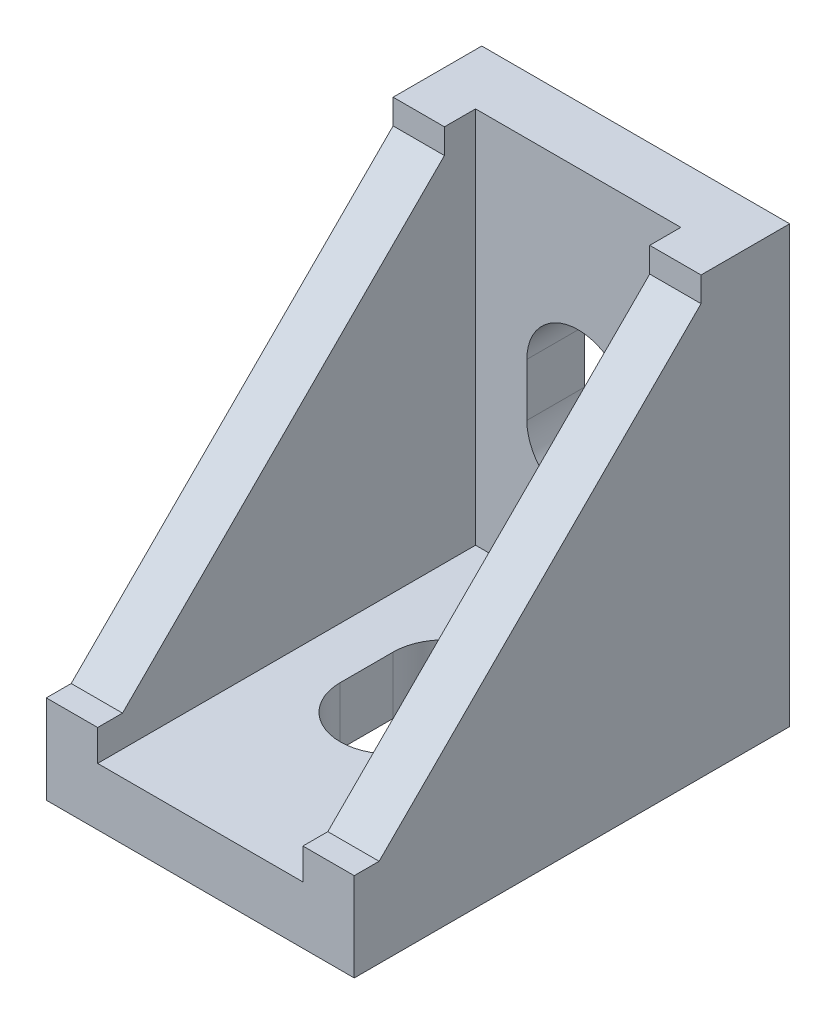
SolidWorks part; units mm, degrees
material "Alumina"
ref_plane "Front Plane" through (0, 0, 0) normal (0, 0, 1) x (1, 0, 0)
ref_plane "Top Plane" through (0, 0, 0) normal (0, 1, 0) x (1, 0, 0)
ref_plane "Right Plane" through (0, 0, 0) normal (1, 0, 0) x (0, 0, -1)
sketch "Sketch1" plane through (0, 0, 0) normal (0, 0, 1) x (1, 0, 0)
  line L0 (9.9, 15.7) -> (9.9, 12.3) construction
  line L1 (0, 0) -> (19.8, 0)
  line L2 (0, 0) -> (0, 28)
  line L3 (0, 28) -> (19.8, 28)
  line L4 (19.8, 0) -> (19.8, 28)
  line L5 (13.2, 15.7) -> (13.2, 12.3)
  line L6 (6.6, 15.7) -> (6.6, 12.3)
  arc A0 (13.2, 15.7) -> (6.6, 15.7) centre (9.9, 15.7) ccw
  arc A1 (6.6, 12.3) -> (13.2, 12.3) centre (9.9, 12.3) ccw
  point P7 (9.9, 14)
  point P12 (9.9, 19)
  point P13 (9.9, 9)
  point P15 (9.9, 28)
  point P17 (19.8, 14)
  dimension "D4" = 10
  dimension "D1" = 19.8
  dimension "D2" = 28
  dimension "D3" = 6.6
extrude "Boss-Extrude1" add sketch "Sketch1" along normal blind 3.7
sketch "Sketch2" plane through (0, 0, 3.7) normal (0, 0, 1) x (1, 0, 0)
  line L0 (19.8, 0) -> (19.8, 28) construction
  line L1 (0, 0) -> (19.8, 0)
  line L2 (0, 0) -> (0, 3.7)
  line L3 (0, 3.7) -> (19.8, 3.7)
  line L4 (19.8, 0) -> (19.8, 3.7)
  dimension "D1" = 3.7
extrude "Boss-Extrude2" add sketch "Sketch2" along normal blind 24.3
sketch "Sketch3" plane through (0, 3.7, 0) normal (0, 1, 0) x (1, 0, 0)
  line L0 (9.9, -12.3) -> (9.9, -15.7) construction
  line L1 (13.2, -12.3) -> (13.2, -15.7)
  line L2 (6.6, -12.3) -> (6.6, -15.7)
  line L3 (19.8, -28) -> (0, -28) construction
  line L5 (19.8, -28) -> (19.8, 0) construction
  arc A0 (13.2, -12.3) -> (6.6, -12.3) centre (9.9, -12.3) ccw
  arc A1 (6.6, -15.7) -> (13.2, -15.7) centre (9.9, -15.7) ccw
  point P2 (9.9, -14)
  point P7 (9.9, -9)
  point P8 (9.9, -19)
  point P12 (9.9, -28)
  point P18 (19.8, -14)
  dimension "D1" = 6.6
  dimension "D2" = 10
extrude "Cut-Extrude1" cut sketch "Sketch3" against normal blind 9
sketch "Sketch4" plane through (19.8, 0, 0) normal (1, 0, 0) x (0, 0, -1)
  line L1 (-3.7, 26.4) -> (-3.7, 3.7)
  line L2 (-3.7, 3.7) -> (-26.4, 3.7)
  line L3 (-3.7, 28) -> (-5.7, 28)
  line L4 (-5.7, 28) -> (-5.7, 26.4)
  line L5 (-28, 3.7) -> (-28, 5.7)
  line L6 (-28, 5.7) -> (-26.4, 5.7)
  line L7 (-26.4, 5.7) -> (-5.7, 26.4)
  line L8 (-3.7, 26.4) -> (-3.7, 28)
  line L9 (-26.4, 3.7) -> (-28, 3.7)
  dimension "D1" = 2
  dimension "D2" = 22.7
  dimension "D3" = 2
  dimension "D4" = 22.7
extrude "Boss-Extrude3" add sketch "Sketch4" against normal blind 3.3
sketch "Sketch5" plane through (0, 0, 0) normal (-1, 0, 0) x (0, 0, 1)
  line L0 (3.7, 26) -> (3.7, 3.7)
  line L1 (3.7, 3.7) -> (26, 3.7)
  line L3 (3.7, 26) -> (3.7, 28)
  line L4 (3.7, 28) -> (5.7, 28)
  line L5 (5.7, 28) -> (5.7, 26.4)
  line L6 (5.7, 26.4) -> (26.4, 5.7)
  line L7 (26.4, 5.7) -> (28, 5.7)
  line L8 (28, 5.7) -> (28, 3.7)
  line L9 (28, 3.7) -> (26, 3.7)
  dimension "D1" = 22.3
  dimension "D2" = 22.3
extrude "Boss-Extrude4" add sketch "Sketch5" against normal blind 3.3
sketch "Sketch6" plane through (0, 0, 0) normal (0, -1, 0) x (-1, 0, 0)
  line L0 (-9.3, -23.9) -> (-10.5, -23.9) construction
  line L1 (-9.3, -25.5) -> (-10.5, -25.5)
  line L2 (-9.3, -22.3) -> (-10.5, -22.3)
  line L3 (-9.45, -2.45) -> (-10.35, -2.45) construction
  line L4 (-9.45, -4.2) -> (-10.35, -4.2)
  line L5 (-9.45, -0.7) -> (-10.35, -0.7)
  line L6 (0, -28) -> (-19.8, -28) construction
  arc A0 (-9.3, -25.5) -> (-9.3, -22.3) centre (-9.3, -23.9) ccw
  arc A1 (-10.5, -22.3) -> (-10.5, -25.5) centre (-10.5, -23.9) ccw
  arc A2 (-9.45, -4.2) -> (-9.45, -0.7) centre (-9.45, -2.45) ccw
  arc A3 (-10.35, -0.7) -> (-10.35, -4.2) centre (-10.35, -2.45) ccw
  arc A6 (-6.6, -12.3) -> (-13.2, -12.3) centre (-9.9, -12.3) ccw construction
  point P2 (-9.9, -23.9)
  point P7 (-9.9, -2.45)
  point P14 (-7.7, -23.9)
  point P15 (-12.1, -23.9)
  point P16 (-12.1, -2.45)
  point P19 (-9.9, -28)
  point P27 (-9.9, -9)
  point P28 (-7.7, -2.45)
  dimension "D1" = 4.4
  dimension "D2" = 3.2
  dimension "D3" = 5.7
  dimension "D4" = 8.3
  dimension "D5" = 3.5
  dimension "D6" = 4.4
extrude "Boss-Extrude5" add sketch "Sketch6" along normal blind 2.1
sketch "Sketch7" plane through (0, 0, 0) normal (0, 0, -1) x (-1, 0, 0)
  line L0 (-10.5, 23.9) -> (-9.3, 23.9) construction
  line L1 (-10.5, 25.5) -> (-9.3, 25.5)
  line L2 (-10.5, 22.3) -> (-9.3, 22.3)
  line L3 (-10.35, 2.45) -> (-9.45, 2.45) construction
  line L4 (-10.35, 4.2) -> (-9.45, 4.2)
  line L5 (-10.35, 0.7) -> (-9.45, 0.7)
  line L6 (-19.8, 28) -> (0, 28) construction
  arc A0 (-10.5, 25.5) -> (-10.5, 22.3) centre (-10.5, 23.9) ccw
  arc A1 (-9.3, 22.3) -> (-9.3, 25.5) centre (-9.3, 23.9) ccw
  arc A2 (-10.35, 4.2) -> (-10.35, 0.7) centre (-10.35, 2.45) ccw
  arc A3 (-9.45, 0.7) -> (-9.45, 4.2) centre (-9.45, 2.45) ccw
  arc A5 (-6.6, 15.7) -> (-13.2, 15.7) centre (-9.9, 15.7) ccw construction
  arc A6 (-13.2, 12.3) -> (-6.6, 12.3) centre (-9.9, 12.3) ccw construction
  point P2 (-9.9, 23.9)
  point P7 (-9.9, 2.45)
  point P17 (-9.9, 9)
  point P21 (-9.9, 19)
  point P22 (-12.1, 23.9)
  point P23 (-7.7, 23.9)
  point P24 (-12.1, 2.45)
  point P25 (-7.7, 2.45)
  dimension "D1" = 3.5
  dimension "D2" = 8.3
  dimension "D3" = 5.7
  dimension "D4" = 3.2
  dimension "D5" = 4.4
  dimension "D6" = 4.4
  dimension "D7" = 6.5
extrude "Boss-Extrude6" add sketch "Sketch7" along normal blind 1.5
